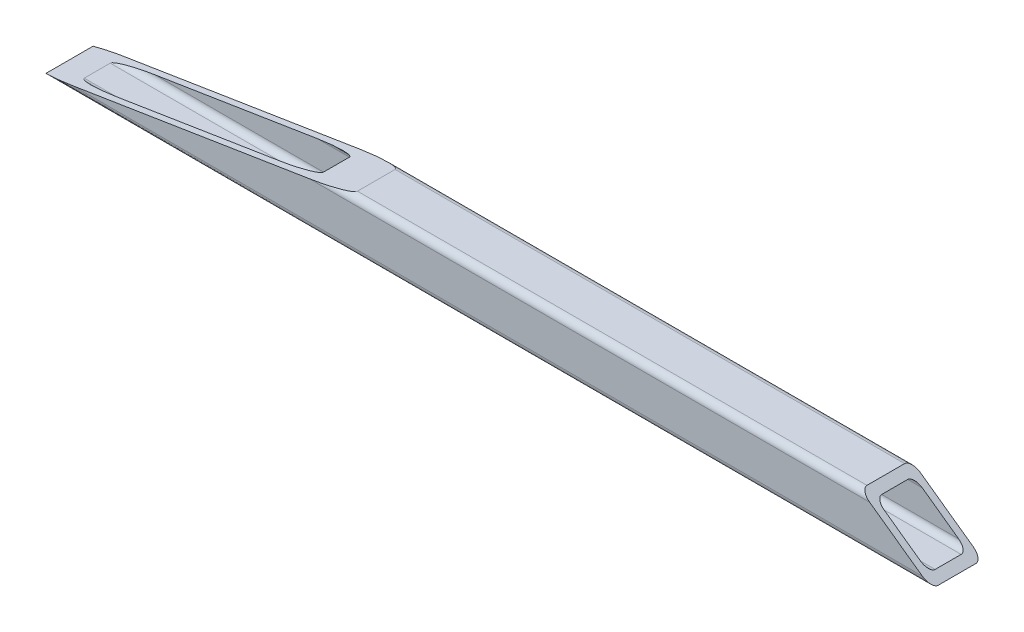
SolidWorks part; units mm, degrees
ref_plane "Front Plane" through (0, 0, 0) normal (0, 0, 1) x (1, 0, 0)
ref_plane "Top Plane" through (0, 0, 0) normal (0, 1, 0) x (1, 0, 0)
ref_plane "Right Plane" through (0, 0, 0) normal (1, 0, 0) x (0, 0, -1)
sketch "Sketch1" plane through (0, 0, 0) normal (1, 0, 0) x (0, 0, -1)
  line L0 (2.3349, -0.9671) -> (21.1309, -0.9671)
  line L1 (-0.9671, 2.3349) -> (-0.9671, 21.1309)
  line L2 (2.3349, 24.4329) -> (21.1309, 24.4329)
  line L3 (24.4329, 2.3349) -> (24.4329, 21.1309)
  line L4 (5.2559, 2.2079) -> (18.2099, 2.2079)
  line L5 (2.2079, 5.2559) -> (2.2079, 18.2099)
  line L6 (5.2559, 21.2579) -> (18.2099, 21.2579)
  line L7 (21.2579, 5.2559) -> (21.2579, 18.2099)
  arc A0 (18.2099, 21.2579) -> (21.2579, 18.2099) centre (18.2099, 18.2099) cw
  arc A1 (18.2099, 2.2079) -> (21.2579, 5.2559) centre (18.2099, 5.2559) ccw
  arc A2 (5.2559, 2.2079) -> (2.2079, 5.2559) centre (5.2559, 5.2559) cw
  arc A3 (2.2079, 18.2099) -> (5.2559, 21.2579) centre (5.2559, 18.2099) cw
  arc A4 (21.1309, -0.9671) -> (24.4329, 2.3349) centre (21.1309, 2.3349) ccw
  arc A5 (2.3349, -0.9671) -> (-0.9671, 2.3349) centre (2.3349, 2.3349) cw
  arc A6 (-0.9671, 21.1309) -> (2.3349, 24.4329) centre (2.3349, 21.1309) cw
  arc A7 (21.1309, 24.4329) -> (24.4329, 21.1309) centre (21.1309, 21.1309) cw
  point P8 (11.7329, 21.2579)
  point P9 (11.7329, 24.4329)
  point P10 (-0.9671, 11.7329)
  point P11 (2.2079, 11.7329)
  point P29 (0, 0)
  dimension "D2" = 3.048
  dimension "D3" = 3.302
  dimension "D1" = 3.175
  dimension "D4" = 25.4
extrude "Boss-Extrude1" add sketch "Sketch1" along normal blind 442.722
sketch "Sketch3" plane through (0, 0, 0.9671) normal (0, 0, 1) x (1, 0, 0)
  line L0 (0, 0) -> (153.035, 24.4329)
  line L1 (442.722, 24.4329) -> (0, 24.4329) construction
  line L2 (153.035, 24.4329) -> (0, 24.4329)
  line L3 (0, 24.4329) -> (0, 0)
  line L4 (442.722, 24.4329) -> (442.722, -0.9671)
  line L5 (442.722, -0.9671) -> (407.1765, 24.4329)
  line L6 (407.1765, 24.4329) -> (442.722, 24.4329)
  dimension "D1" = 153.035
  dimension "D2" = 35.5455
extrude "Cut-Extrude1" cut sketch "Sketch3" against normal through all
